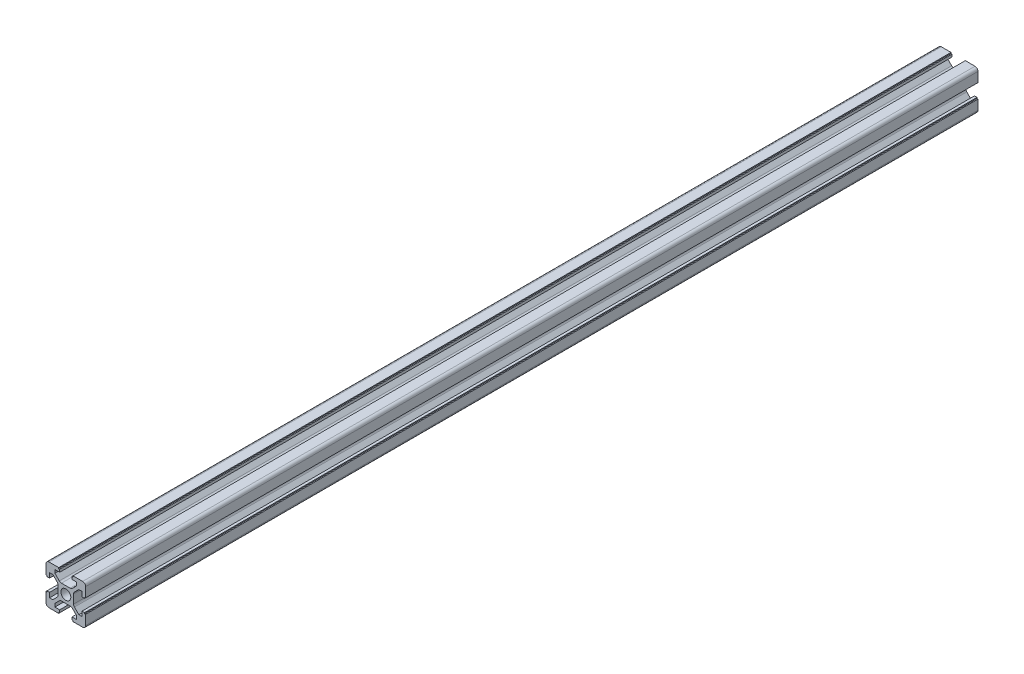
SolidWorks part; units mm, degrees
material "6061 合金"
ref_plane "前视基准面" through (0, 0, 0) normal (0, 0, 1) x (1, 0, 0)
ref_plane "上视基准面" through (0, 0, 0) normal (0, 1, 0) x (1, 0, 0)
ref_plane "右视基准面" through (0, 0, 0) normal (1, 0, 0) x (0, 0, -1)
sketch "草图1" plane through (0, 0, 0) normal (0, 0, 1) x (1, 0, 0)
  line L0 (-6.5607, 5.5) -> (-4.3393, 3.2787)
  line L1 (-3.9, 2.218) -> (-3.9, -2.218)
  line L2 (-4.3393, -3.2787) -> (-6.5607, -5.5)
  line L3 (-6.5607, -5.5) -> (-8.2, -5.5)
  line L4 (-8.2, -5.5) -> (-8.2, -3.1)
  line L5 (-8.2, -3.1) -> (-9.5, -3.1)
  line L6 (-9.5, -3.1) -> (-9.5, -3.6)
  line L7 (-9.5, -3.6) -> (-10, -3.6)
  line L8 (-10, -3.6) -> (-10, -8.5)
  line L9 (-6.5607, 5.5) -> (-8.2, 5.5)
  line L10 (-8.2, 5.5) -> (-8.2, 3.1)
  line L11 (-8.2, 3.1) -> (-9.5, 3.1)
  line L12 (-9.5, 3.1) -> (-9.5, 3.6)
  line L13 (-9.5, 3.6) -> (-10, 3.6)
  line L14 (-10, 3.6) -> (-10, 8.5)
  line L15 (5.5, 6.5607) -> (3.2787, 4.3393)
  line L16 (2.218, 3.9) -> (-2.218, 3.9)
  line L17 (-3.2787, 4.3393) -> (-5.5, 6.5607)
  line L18 (-5.5, 6.5607) -> (-5.5, 8.2)
  line L19 (-5.5, 8.2) -> (-3.1, 8.2)
  line L20 (-3.1, 8.2) -> (-3.1, 9.5)
  line L21 (-3.1, 9.5) -> (-3.6, 9.5)
  line L22 (-3.6, 9.5) -> (-3.6, 10)
  line L23 (-3.6, 10) -> (-8.5, 10)
  line L24 (5.5, 6.5607) -> (5.5, 8.2)
  line L25 (5.5, 8.2) -> (3.1, 8.2)
  line L26 (3.1, 8.2) -> (3.1, 9.5)
  line L27 (3.1, 9.5) -> (3.6, 9.5)
  line L28 (3.6, 9.5) -> (3.6, 10)
  line L29 (3.6, 10) -> (8.5, 10)
  line L30 (6.5607, -5.5) -> (4.3393, -3.2787)
  line L31 (3.9, -2.218) -> (3.9, 2.218)
  line L32 (4.3393, 3.2787) -> (6.5607, 5.5)
  line L33 (6.5607, 5.5) -> (8.2, 5.5)
  line L34 (8.2, 5.5) -> (8.2, 3.1)
  line L35 (8.2, 3.1) -> (9.5, 3.1)
  line L36 (9.5, 3.1) -> (9.5, 3.6)
  line L37 (9.5, 3.6) -> (10, 3.6)
  line L38 (10, 3.6) -> (10, 8.5)
  line L39 (6.5607, -5.5) -> (8.2, -5.5)
  line L40 (8.2, -5.5) -> (8.2, -3.1)
  line L41 (8.2, -3.1) -> (9.5, -3.1)
  line L42 (9.5, -3.1) -> (9.5, -3.6)
  line L43 (9.5, -3.6) -> (10, -3.6)
  line L44 (10, -3.6) -> (10, -8.5)
  line L45 (-5.5, -6.5607) -> (-3.2787, -4.3393)
  line L46 (-2.218, -3.9) -> (2.218, -3.9)
  line L47 (3.2787, -4.3393) -> (5.5, -6.5607)
  line L48 (5.5, -6.5607) -> (5.5, -8.2)
  line L49 (5.5, -8.2) -> (3.1, -8.2)
  line L50 (3.1, -8.2) -> (3.1, -9.5)
  line L51 (3.1, -9.5) -> (3.6, -9.5)
  line L52 (3.6, -9.5) -> (3.6, -10)
  line L53 (3.6, -10) -> (8.5, -10)
  line L54 (-5.5, -6.5607) -> (-5.5, -8.2)
  line L55 (-5.5, -8.2) -> (-3.1, -8.2)
  line L56 (-3.1, -8.2) -> (-3.1, -9.5)
  line L57 (-3.1, -9.5) -> (-3.6, -9.5)
  line L58 (-3.6, -9.5) -> (-3.6, -10)
  line L59 (-3.6, -10) -> (-8.5, -10)
  line L60 (0, 0) -> (-3.9, 2.8393) construction
  line L61 (0, 0) -> (2.8393, 3.9) construction
  arc A0 (4.3393, -3.2787) -> (3.9, -2.218) centre (5.4, -2.218) cw
  arc A1 (3.9, 2.218) -> (4.3393, 3.2787) centre (5.4, 2.218) cw
  arc A2 (3.2787, 4.3393) -> (2.218, 3.9) centre (2.218, 5.4) cw
  arc A3 (-2.218, 3.9) -> (-3.2787, 4.3393) centre (-2.218, 5.4) cw
  arc A4 (-4.3393, 3.2787) -> (-3.9, 2.218) centre (-5.4, 2.218) cw
  arc A5 (-3.9, -2.218) -> (-4.3393, -3.2787) centre (-5.4, -2.218) cw
  arc A6 (2.218, -3.9) -> (3.2787, -4.3393) centre (2.218, -5.4) cw
  arc A7 (-3.2787, -4.3393) -> (-2.218, -3.9) centre (-2.218, -5.4) cw
  arc A8 (-10, -8.5) -> (-8.5, -10) centre (-8.5, -8.5) ccw
  arc A9 (10, -8.5) -> (8.5, -10) centre (8.5, -8.5) cw
  arc A10 (8.5, 10) -> (10, 8.5) centre (8.5, 8.5) cw
  arc A11 (-10, 8.5) -> (-8.5, 10) centre (-8.5, 8.5) cw
  circle A12 centre (0, 0) radius 2.5
  point P27 (-3.9, 0)
  point P75 (2.8393, 3.9)
  dimension "D12" = 1.5
  dimension "D13" = 5
  dimension "D2" = 20
  dimension "D3" = 7.2
  dimension "D4" = 6.2
  dimension "D5" = 7.8
  dimension "D6" = 45
  dimension "D7" = 1.5
  dimension "D8" = 11
  dimension "D9" = 1.8
  dimension "D10" = 0.5
  dimension "D11" = 3.1
  dimension "D1" = 4
extrude "凸台-拉伸1" add sketch "草图1" along normal mid plane 450
sketch "草图2" plane through (0, 10, 0) normal (0, 1, 0) x (1, 0, 0)
  line L0 (2.218, 225) -> (-2.218, 225) construction
  circle A0 centre (0, 215) radius 1.6
  circle A1 centre (0, 195) radius 1.6
  circle A2 centre (0, 175) radius 1.6
  dimension "D1" = 3.2
  dimension "D2" = 10
  dimension "D3" = 20
  dimension "D4" = 20
extrude "切除-拉伸1" cut sketch "草图2" against normal through all
